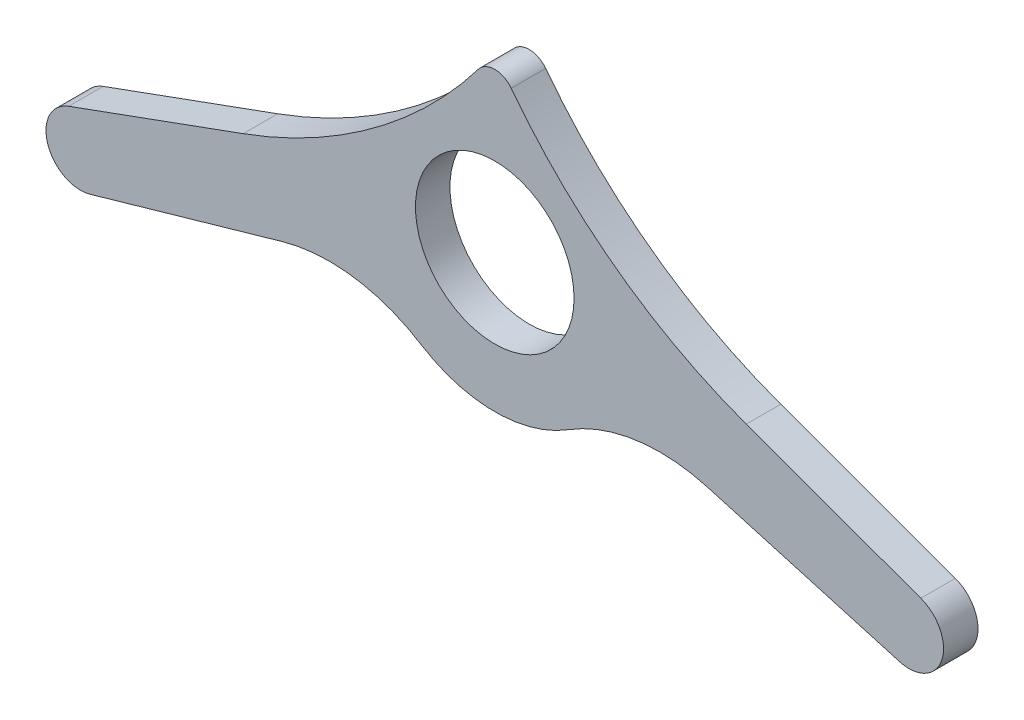
SolidWorks part; units mm, degrees
ref_plane "Front Plane" through (0, 0, 0) normal (0, 0, 1) x (1, 0, 0)
ref_plane "Top Plane" through (0, 0, 0) normal (0, 1, 0) x (1, 0, 0)
ref_plane "Right Plane" through (0, 0, 0) normal (1, 0, 0) x (0, 0, -1)
sketch "Sketch1" plane through (0, 0, 0) normal (0, 0, 1) x (1, 0, 0)
  line L0 (0, 32.4193) -> (0, -33.8996) construction
  line L1 (0, 0) -> (150.0385, 0) construction
  line L2 (0, 0) -> (60.0789, -17.2273) construction
  line L3 (58.7007, -22.0336) -> (30.8635, -14.0515)
  line L4 (61.789, -12.5289) -> (36.4759, -3.3157)
  line L5 (-61.789, -12.5289) -> (-36.4759, -3.3157)
  line L6 (-58.7007, -22.0336) -> (-30.8635, -14.0515)
  circle A0 centre (0, 0) radius 11.5
  arc A1 (-10.6545, -16.9258) -> (10.6545, -16.9258) centre (0, 0) ccw
  arc A2 (2.3895, 21.8139) -> (-2.3895, 21.8139) centre (0, 20) ccw
  circle A3 centre (0, 0) radius 62.5 construction
  arc A6 (58.5095, -21.9747) -> (61.2637, -12.3697) centre (60.0789, -17.2273) ccw
  arc A7 (36.4759, -3.3157) -> (2.3895, 21.8139) centre (62.1274, 67.1613) cw
  arc A8 (30.8635, -14.0515) -> (10.6545, -16.9258) centre (23.9726, -38.083) ccw
  arc A9 (-30.8635, -14.0515) -> (-10.6545, -16.9258) centre (-23.9726, -38.083) cw
  arc A10 (-36.4759, -3.3157) -> (-2.3895, 21.8139) centre (-62.1274, 67.1613) ccw
  arc A11 (-58.5095, -21.9747) -> (-61.2637, -12.3697) centre (-60.0789, -17.2273) cw
  point P20 (10.2031, -17.2273)
  point P21 (10.8555, -16.7976)
  point P22 (33.4617, -14.7965)
  dimension "D1" = 16
  dimension "D2" = 10
  dimension "D3" = 125
  dimension "D4" = 40
  dimension "D5" = 23
  dimension "D7" = 75
  dimension "D8" = 6
  dimension "D9" = 25
  dimension "D6" = 4
extrude "Boss-Extrude1" add sketch "Sketch1" along normal blind 5
